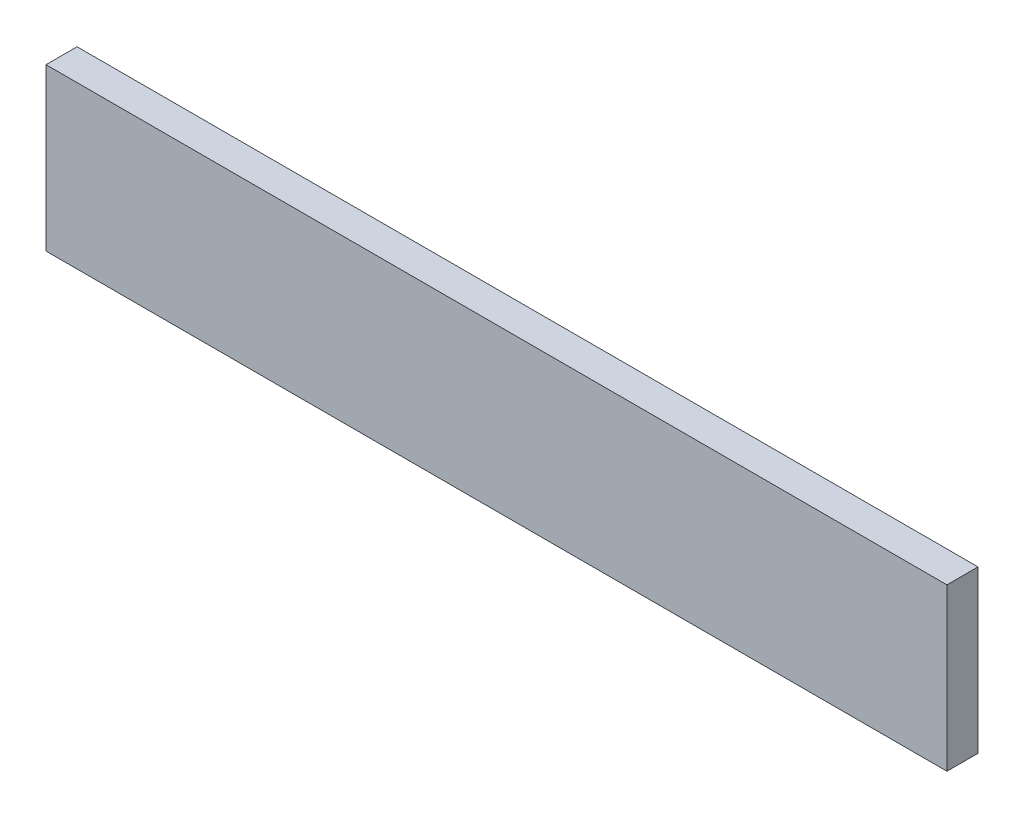
SolidWorks part; units mm, degrees
material "Pine"
ref_plane "Front Plane" through (0, 0, 0) normal (0, 0, 1) x (1, 0, 0)
ref_plane "Top Plane" through (0, 0, 0) normal (0, 1, 0) x (1, 0, 0)
ref_plane "Right Plane" through (0, 0, 0) normal (1, 0, 0) x (0, 0, -1)
sketch "Sketch1" plane through (0, 0, 0) normal (0, 0, 1) x (1, 0, 0)
  line L1 (-276.225, -49.5008) -> (276.225, -49.5008)
  line L2 (-276.225, -49.5008) -> (-276.225, 49.5008)
  line L3 (-276.225, 49.5008) -> (276.225, 49.5008)
  line L4 (276.225, -49.5008) -> (276.225, 49.5008)
  line L5 (-276.225, -49.5008) -> (276.225, 49.5008) construction
  line L6 (-276.225, 49.5008) -> (276.225, -49.5008) construction
  point P0 (0, 0)
  dimension "D1" = 552.45
  dimension "D2" = 99.0016
extrude "Boss-Extrude1" add sketch "Sketch1" along normal blind 19.05
equation "\"2.5325‬\"=6.68551"
